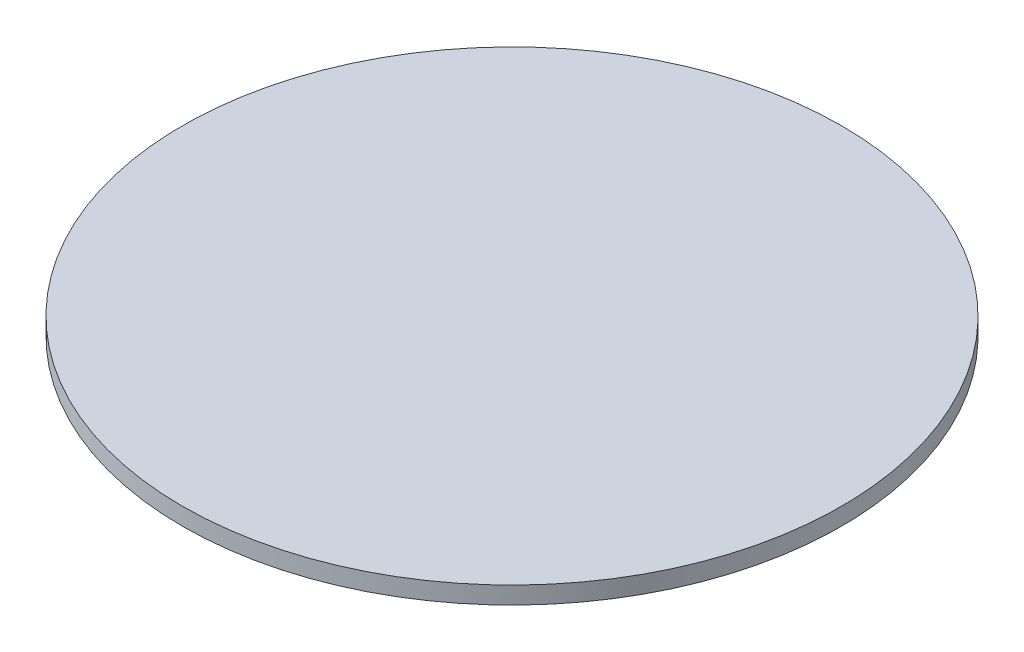
SolidWorks part; units mm, degrees
ref_plane "Front Plane" through (0, 0, 0) normal (0, 0, 1) x (1, 0, 0)
ref_plane "Top Plane" through (0, 0, 0) normal (0, 1, 0) x (1, 0, 0)
ref_plane "Right Plane" through (0, 0, 0) normal (1, 0, 0) x (0, 0, -1)
sketch "Sketch1" plane through (0, 0, 0) normal (0, 1, 0) x (1, 0, 0)
  circle A0 centre (0, 0) radius 19
  dimension "D1" = 38
extrude "Boss-Extrude1" add sketch "Sketch1" along normal blind 1
